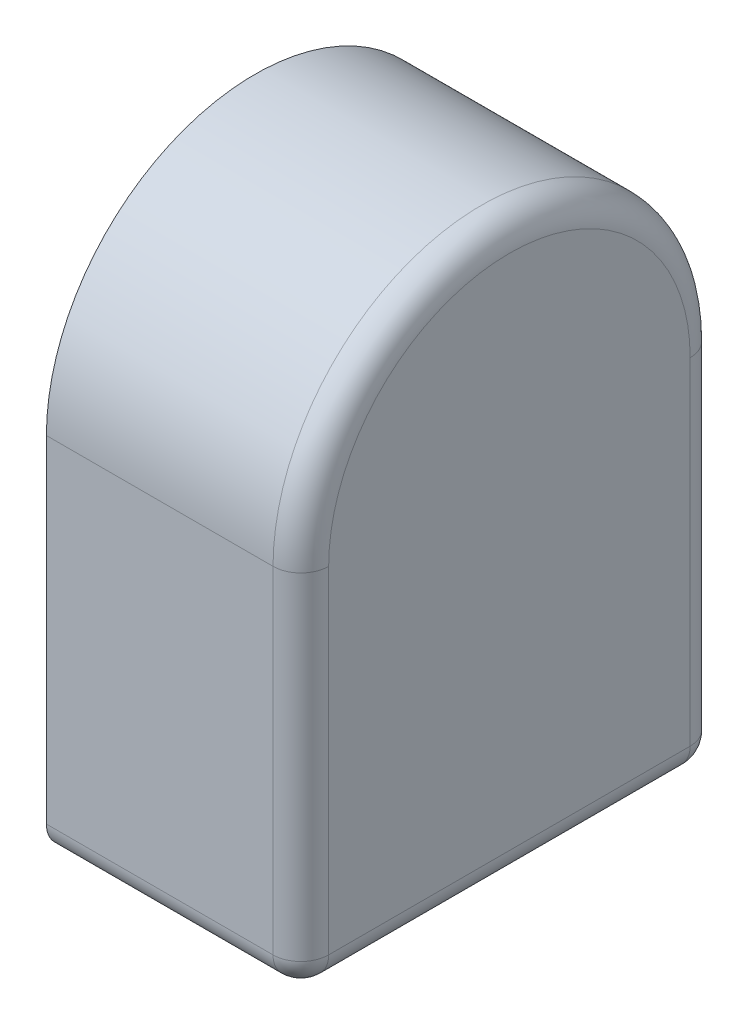
SolidWorks part; units mm, degrees
ref_plane "Front Plane" through (0, 0, 0) normal (0, 0, 1) x (1, 0, 0)
ref_plane "Top Plane" through (0, 0, 0) normal (0, 1, 0) x (1, 0, 0)
ref_plane "Right Plane" through (0, 0, 0) normal (1, 0, 0) x (0, 0, -1)
sketch "Sketch1" plane through (0, 0, 0) normal (1, 0, 0) x (0, 0, -1)
  line L1 (0, 0) -> (30, 0)
  line L2 (0, 0) -> (0, 26.2)
  line L4 (30, 0) -> (30, 26.2)
  arc A1 (0, 26.2) -> (30, 26.2) centre (15, 26.2) cw
  dimension "D1" = 26.2
  dimension "D2" = 30
extrude "Extrude1" add sketch "Sketch1" along normal blind 18.3
sketch "Sketch2" plane through (0, 0, 0) normal (-1, 0, 0) x (0, 0, 1)
  circle A0 centre (-15, 26.2) radius 3.01
  dimension "D1" = 6.02
extrude "Cut-Extrude1" cut sketch "Sketch2" against normal blind 15.5
fillet "Fillet1" radius 2 6 edges at (18.3, 41.2, -15) (18.3, 13.1, -30) (18.3, 0, -15) (18.3, 13.1, 0) (9.15, 0, -30) (9.15, 0, 0)
